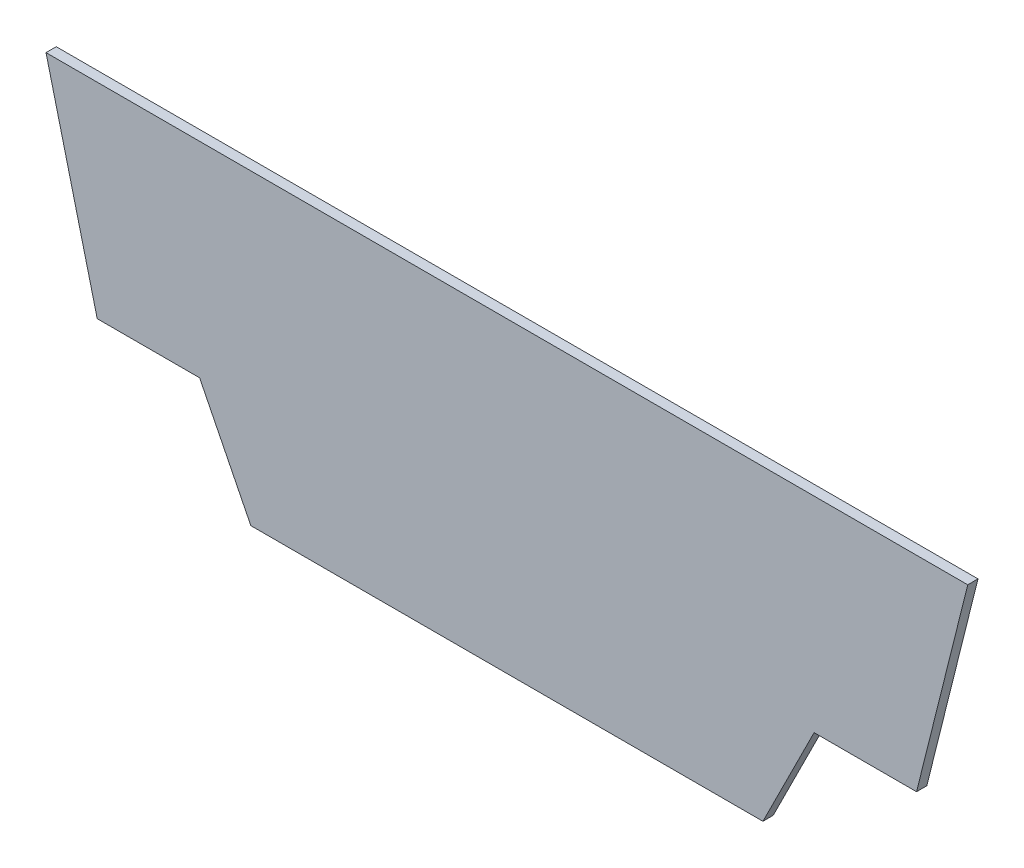
SolidWorks part; units mm, degrees
ref_plane "前视基准面" through (0, 0, 0) normal (0, 0, 1) x (1, 0, 0)
ref_plane "上视基准面" through (0, 0, 0) normal (0, 1, 0) x (1, 0, 0)
ref_plane "右视基准面" through (0, 0, 0) normal (1, 0, 0) x (0, 0, -1)
other "Configuration Table"
sketch "草图1" plane through (0, 0, 0) normal (0, 0, 1) x (1, 0, 0)
  line L0 (0, 0) -> (-50, 0)
  line L5 (-50, 0) -> (-60, 20)
  line L6 (-60, 20) -> (-80, 20)
  line L7 (-80, 20) -> (-90, 60)
  line L8 (-90, 60) -> (-88, 60)
  line L9 (-88, 60) -> (-78.5084, 22.0335)
  line L10 (-78.5084, 22.0335) -> (-58.7016, 22.0335)
  line L14 (0, 0) -> (0, 2)
  line L15 (-48.7136, 2) -> (-58.7016, 22.0335)
  line L16 (-48.7136, 2) -> (0, 2)
sketch "草图2" plane through (0, 0, 0) normal (0, 0, 1) x (1, 0, 0)
  line L0 (-90, 60) -> (90, 60)
  line L1 (50, 0) -> (-50, 0)
  line L2 (-50, 0) -> (-60, 20)
  line L3 (-60, 20) -> (-80, 20)
  line L4 (-80, 20) -> (-90, 60)
  line L11 (80, 20) -> (90, 60)
  line L14 (60, 20) -> (80, 20)
  line L15 (50, 0) -> (60, 20)
  point P29 (0, 2)
extrude "凸台-拉伸1" add sketch "草图2" along normal blind 2
